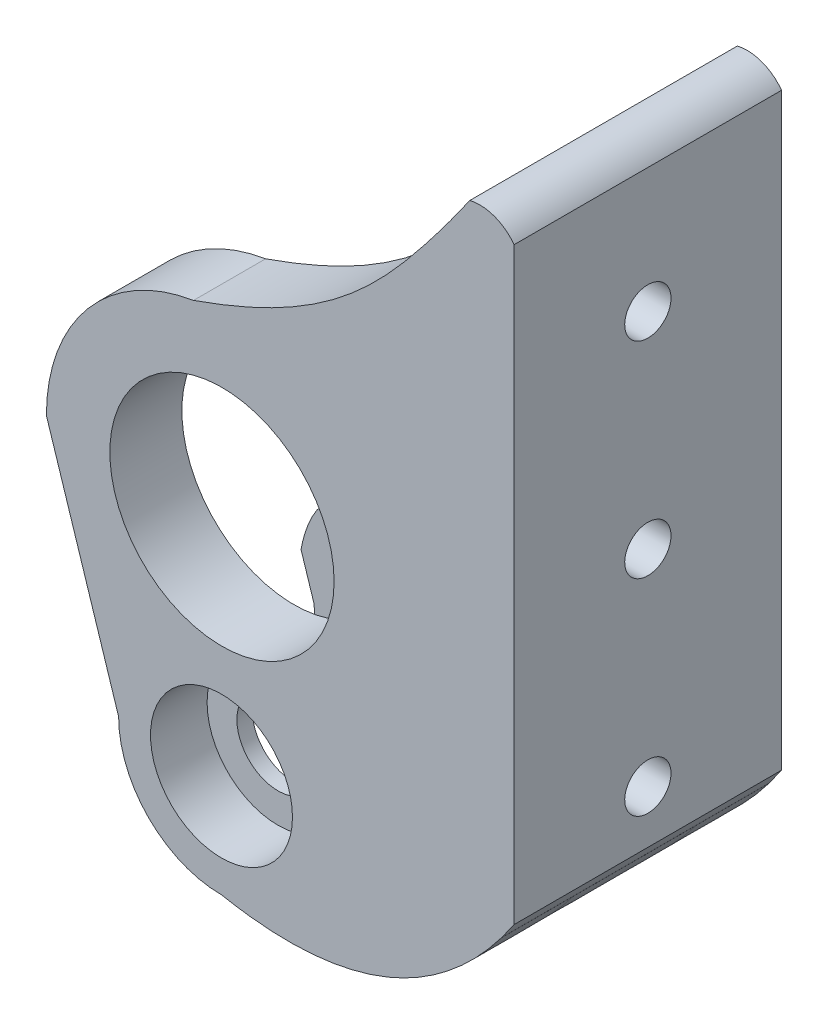
SolidWorks part; units mm, degrees
ref_plane "Front Plane" through (0, 0, 0) normal (0, 0, 1) x (1, 0, 0)
ref_plane "Top Plane" through (0, 0, 0) normal (0, 1, 0) x (1, 0, 0)
ref_plane "Right Plane" through (0, 0, 0) normal (1, 0, 0) x (0, 0, -1)
sketch "Sketch1" plane through (0, 0, 0) normal (0, 0, 1) x (1, 0, 0)
  line L0 (-124.2968, 47.657) -> (-117.2775, 25.8121)
  line L1 (-80.0553, 84.3442) -> (-80.0553, 25.8121)
  circle A0 centre (-107.23, 47.657) radius 10.9
  circle A1 centre (-107.2775, 25.8121) radius 6.9
  arc A2 (-109.9929, 64.4987) -> (-124.2968, 47.657) centre (-107.23, 47.657) ccw
  arc A3 (-117.2774, 25.8556) -> (-107.2775, 15.8121) centre (-107.2775, 25.8121) ccw
  arc A4 (-83.6647, 85.5315) -> (-80.0553, 84.3442) centre (-82.0553, 84.3442) cw
  spline S0 degree 3 poles (-109.9929, 64.4987) (-95.7368, 69.4712) (-91.1309, 75.4105) (-83.6647, 85.5315) knots 0 0 0 0 0.858728 0.858728 0.858728 0.858728
  spline S1 degree 2 poles (-80.0553, 25.8121) (-90.1657, 12.4948) (-107.2775, 15.8121) knots 0 0 0 1 1 1
extrude "Boss-Extrude1" add sketch "Sketch1" along normal blind 7 contours S1 L1 A4 S0 A2 L0 A3 A1 A0
sketch "Sketch2" plane through (0, 0, 7) normal (0, 0, 1) x (1, 0, 0)
  line L0 (-85.0553, 83.6537) -> (-85.0553, 20.5833)
  line L2 (-80.0553, 25.8121) -> (-80.0553, 84.3442)
  line L3 (-121.1024, 37.7156) -> (-115.4058, 19.987)
  line L4 (-80.0553, 25.8121) -> (-80.0553, 84.3442)
  arc A3 (-80.0553, 84.3442) -> (-83.6647, 85.5315) centre (-82.0553, 84.3442) ccw
  arc A4 (-109.9929, 64.4987) -> (-121.1024, 37.7156) centre (-107.23, 47.657) ccw
  arc A5 (-115.4058, 19.987) -> (-107.2775, 15.8121) centre (-107.2775, 25.8121) ccw
  arc A6 (-80.0553, 84.3442) -> (-83.6647, 85.5315) centre (-82.0553, 84.3442) ccw
  parabola Q1 (-107.2775, 15.8121) -> (-80.0553, 25.8121) focus (-95.4224, 27.7636) apex (-90.9126, 17.0487)
  parabola Q2 (-85.0553, 20.5833) -> (-80.0553, 25.8121) focus (-95.4224, 27.7636) apex (-90.9126, 17.0487)
  spline S1 degree 3 poles (1729.154, 923.3668) (-1823.5702, -431.2559) (1701.6954, 411.3928) (-2085.4377, -246.693) knots -4.229152 -4.229152 -4.229152 -4.229152 4.76838 4.76838 4.76838 4.76838 only from (-83.6647, 85.5315) to (-109.9929, 64.4987)
  spline S2 degree 3 poles (-83.6647, 85.5315) (-84.1387, 84.889) (-84.6011, 84.2633) (-85.0553, 83.6537) knots 0 0 0 0 0.054514 0.054514 0.054514 0.054514
  dimension "D2" = 5
  dimension "D1" = 0
extrude "Boss-Extrude2" add sketch "Sketch2" along normal blind 12
ref_plane "Plane1" through (0, 0, 13) normal (0, 0, 1) x (1, 0, 0)
mirror "Mirror1" about plane through (0, 0, 13) normal (0, 0, 1) of "Boss-Extrude1"
sketch "Sketch3" plane through (0, 0, 0) normal (0, 0, -1) x (-1, 0, 0)
  line L0 (124.2968, 47.657) -> (117.2775, 25.8121) construction
  line L1 (92.8505, 74.3977) -> (144.5312, 88.8658)
  line L2 (144.5312, 88.8658) -> (118.5461, 29.7602)
  circle A0 centre (107.23, 47.657) radius 10.9 construction
  arc A1 (96.33, 47.657) -> (107.23, 36.757) centre (107.23, 47.657) ccw
  spline S0 degree 2 poles (92.8505, 74.3977) (90.4236, 60.1608) (96.33, 47.657) knots 0 0 0 1 1 1
  spline S1 degree 3 poles (109.9929, 64.4987) (95.7368, 69.4712) (91.1309, 75.4105) (83.6647, 85.5315) knots 0 0 0 0 0.858728 0.858728 0.858728 0.858728 construction
  spline S2 degree 2 poles (107.23, 36.757) (116.8643, 38.6004) (118.5461, 29.7602) knots 0 0 0 1 1 1
extrude "Cut-Extrude1" cut sketch "Sketch3" against normal blind 13
sketch "Sketch4" plane through (0, 0, 0) normal (0, 0, -1) x (-1, 0, 0)
  line L1 (78.83, 3.461) -> (78.83, 91.853) construction
  line L2 (83.1328, 86.3442) -> (85.0553, 83.6537)
  line L4 (78.83, 84.7703) -> (78.83, 27.533)
  line L6 (85.0553, 83.6537) -> (85.0553, 20.5833) construction
  line L7 (85.0553, 83.6537) -> (85.0553, 20.5878)
  arc A7 (83.1328, 86.3442) -> (78.83, 84.7703) centre (82.1807, 82.2784) ccw
  parabola Q7 (78.83, 27.533) -> (85.0553, 20.5878) focus (95.4245, 27.7656) apex (90.9128, 17.0515)
extrude "Boss-Extrude3" add sketch "Sketch4" against normal up to vertex (26 mm away) up to point (-80.0553, 25.8121, 26)
sketch "Sketch5" plane through (0, 0, 7) normal (0, 0, 1) x (1, 0, 0)
  circle A0 centre (-107.2775, 25.8121) radius 7.9739
  circle A1 centre (-107.2775, 25.8121) radius 4
  dimension "D1" = 8
extrude "Boss-Extrude4" add sketch "Sketch5" against normal blind 1.5
sketch "Sketch6" plane through (0, 0, 19) normal (0, 0, -1) x (-1, 0, 0)
  circle A0 centre (107.2775, 25.8121) radius 8.4911
  circle A1 centre (107.2775, 25.8121) radius 4
  dimension "D1" = 8
extrude "Boss-Extrude5" add sketch "Sketch6" against normal blind 1.5
sketch "Sketch7" plane through (-85.0553, 0, 0) normal (-1, 0, 0) x (0, 0, 1)
  line L0 (13, -18.42) -> (13, 18.42) construction
  line L1 (19, 83.6537) -> (7, 83.6537) construction
  circle A0 centre (13, 32.6537) radius 2.25
  circle A1 centre (13, 52.6537) radius 2.25
  circle A2 centre (13, 72.6537) radius 2.25
  dimension "D1" = 4.5
  dimension "D2" = 4.5
  dimension "D3" = 4.5
  dimension "D4" = 20
  dimension "D5" = 20
  dimension "D6" = 11
extrude "Cut-Extrude2" cut sketch "Sketch7" against normal through all
scale "Scale1" scale about centroid uniform scaling yes scale factor 1.5
